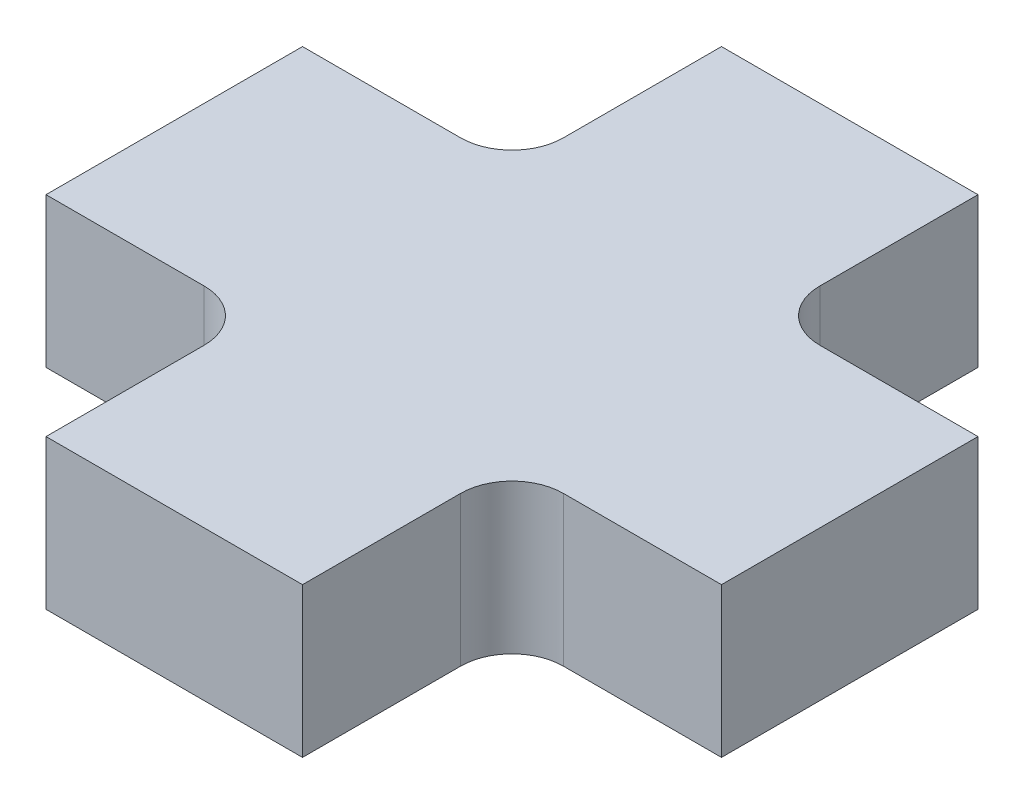
SolidWorks part; units mm, degrees
ref_plane "Front Plane" through (0, 0, 0) normal (0, 0, 1) x (1, 0, 0)
ref_plane "Top Plane" through (0, 0, 0) normal (0, 1, 0) x (1, 0, 0)
ref_plane "Right Plane" through (0, 0, 0) normal (1, 0, 0) x (0, 0, -1)
sketch "Sketch1" plane through (0, 0, 0) normal (0, 1, 0) x (1, 0, 0)
  line L0 (0, 0) -> (0, 7.62)
  line L9 (0, 7.62) -> (6.223, 7.62)
  line L10 (6.223, 7.62) -> (6.223, 13.843)
  line L11 (6.223, 13.843) -> (13.843, 13.843)
  line L12 (13.843, 13.843) -> (13.843, 7.62)
  line L13 (13.843, 7.62) -> (20.066, 7.62)
  line L14 (20.066, 7.62) -> (20.066, 0)
  line L15 (20.066, 0) -> (13.843, 0)
  line L16 (13.843, 0) -> (13.843, -6.223)
  line L17 (13.843, -6.223) -> (6.223, -6.223)
  line L18 (6.223, -6.223) -> (6.223, 0)
  line L19 (6.223, 0) -> (0, 0)
  point P15 (13.843, 7.62)
  dimension "D1" = 20.066
  dimension "D2" = 20.066
  dimension "D3" = 7.62
extrude "Boss-Extrude1" add sketch "Sketch1" along normal blind 4.445
fillet "Fillet1" radius 1.524 4 edges at (13.843, 2.2225, -7.62) (13.843, 2.2225, 0) (6.223, 2.2225, 0) (6.223, 2.2225, -7.62)
